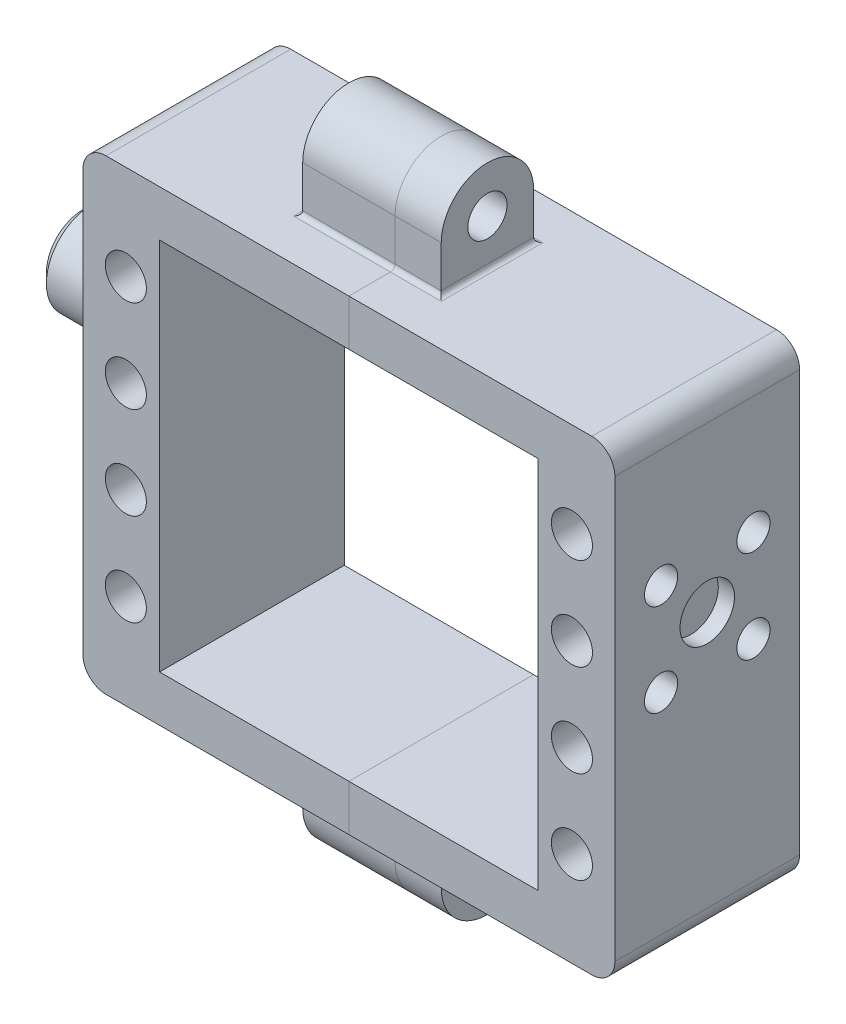
SolidWorks part; units mm, degrees
ref_plane "Front Plane" through (0, 0, 0) normal (0, 0, 1) x (1, 0, 0)
ref_plane "Top Plane" through (0, 0, 0) normal (0, 1, 0) x (1, 0, 0)
ref_plane "Right Plane" through (0, 0, 0) normal (1, 0, 0) x (0, 0, -1)
sketch "Sketch1" plane through (0, 0, 0) normal (0, 0, 1) x (1, 0, 0)
  line L0 (-8.3, -5) -> (49.3, -5)
  line L1 (0, 0) -> (41, 0)
  line L2 (0, 0) -> (0, 40.5)
  line L3 (0, 40.5) -> (41, 40.5)
  line L4 (41, 0) -> (41, 40.5)
  line L5 (49.3, -5) -> (49.3, 45.5)
  line L6 (-8.3, 45.5) -> (49.3, 45.5)
  line L7 (-8.3, -5) -> (-8.3, 45.5)
  line L8 (20.5, 45.5) -> (20.5, -5) construction
  line L10 (-3.65, 20.25) -> (-3.65, 25.25) construction
  line L11 (-3.65, 25.25) -> (-3.65, 35.25) construction
  circle A0 centre (-3.65, 25.25) radius 2.225
  circle A1 centre (-3.65, 35.25) radius 2.225
  circle A2 centre (-3.65, 5.25) radius 2.225
  circle A3 centre (-3.65, 15.25) radius 2.225
  circle A4 centre (44.65, 15.25) radius 2.225
  circle A5 centre (44.65, 5.25) radius 2.225
  circle A6 centre (44.65, 35.25) radius 2.225
  circle A7 centre (44.65, 25.25) radius 2.225
  point P34 (20.5, 20.25)
  dimension "D5" = 4.45
  dimension "D1" = 41
  dimension "D2" = 40.5
  dimension "D4" = 5
  dimension "D6" = 10
  dimension "D3" = 8.3
  dimension "D7" = 8.3
  dimension "D8" = 5
  dimension "D9" = 48.3
  dimension "D10" = 5
  dimension "D11" = 10
  dimension "D12" = 5
extrude "Boss-Extrude1" add sketch "Sketch1" along normal blind 20
fillet "Fillet1" radius 2.5 4 edges at (49.3, 45.5, 10) (49.3, -5, 10) (-8.3, -5, 10) (-8.3, 45.5, 10)
sketch "Sketch2" plane through (49.3, 0, 0) normal (-1, 0, 0) x (0, 0, 1)
  line L0 (20, 33.55) -> (0, 33.55) construction
  line L1 (20, 43) -> (20, -2.5) construction
  line L2 (0, 43) -> (0, -2.5) construction
  circle A0 centre (10, 33.55) radius 3.125
  circle A1 centre (10, 33.55) radius 5.125
  dimension "D1" = 6.25
  dimension "D2" = 38.55
  dimension "D3" = 2
ref_plane "Plane2" through (20.5, 0, 0) normal (-1, 0, 0) x (0, 0, 1)
sketch "Sketch8" plane through (20.5, 0, 0) normal (-1, 0, 0) x (0, 0, 1)
  line L0 (5, 45.5) -> (5, 50.5)
  line L1 (15, -5) -> (15, -10)
  line L2 (0, 45.5) -> (20, 45.5) construction
  line L3 (15, 45.5) -> (5, 45.5)
  line L4 (15, 45.5) -> (15, 50.5)
  line L5 (0, 20.25) -> (20, 20.25) construction
  line L6 (0, 43) -> (0, -2.5) construction
  line L7 (20, 43) -> (20, -2.5) construction
  line L8 (15, -5) -> (5, -5)
  line L9 (5, -5) -> (5, -10)
  arc A0 (15, 50.5) -> (5, 50.5) centre (10, 50.5) ccw
  circle A1 centre (10, 50.5) radius 2.125
  circle A2 centre (10, -10) radius 2.125
  arc A3 (15, -10) -> (5, -10) centre (10, -10) cw
  point P9 (10, 45.5)
  point P25 (10, -5)
  dimension "D1" = 4.25
  dimension "D2" = 10
  dimension "D3" = 5
extrude "Boss-Extrude3" add sketch "Sketch8" against normal blind 5 and the other way blind 10
fillet "Fillet5" radius 0.5 4 edges at (25.5, 45.5, 10) (18, 45.5, 5) (10.5, 45.5, 10) (18, 45.5, 15)
split "Split1" trim tools "Plane2" bodies to split 106 resulting bodies 107 108
sketch "Sketch9" plane through (10.5, 0, 0) normal (-1, 0, 0) x (0, 0, 1)
  line L0 (0, 20.25) -> (20, 20.25) construction
  line L1 (0, 43) -> (0, -2.5) construction
  line L2 (20, 43) -> (20, -2.5) construction
  circle A0 centre (10, 50.5) radius 2.95
  circle A1 centre (10, 50.5) radius 2.125 construction
  circle A2 centre (10, -10) radius 2.95
  dimension "D1" = 5.9
extrude "Cut-Extrude3" cut sketch "Sketch9" against normal up to next (10 mm away)
sketch "Sketch13" plane through (49.3, 0, 0) normal (1, 0, 0) x (0, 0, -1)
  line L0 (-15, 30.25) -> (-5, 20.25) construction
  line L1 (-5, 30.25) -> (-15, 20.25) construction
  line L2 (-20, 25.25) -> (0, 25.25) construction
  line L3 (-20, -2.5) -> (0, -2.5) construction
  circle A0 centre (-15, 30.25) radius 1.8
  circle A1 centre (-5, 30.25) radius 1.8
  circle A2 centre (-15, 20.25) radius 1.8
  circle A3 centre (-5, 20.25) radius 1.8
  point P11 (-10, 25.25)
  point P14 (-10, -2.5)
  dimension "D1" = 3.6
  dimension "D2" = 10
  dimension "D3" = 10
extrude "Cut-Extrude6" cut sketch "Sketch13" against normal up to next (8.3 mm away)
sketch "Sketch14" plane through (41, 0, 0) normal (-1, 0, 0) x (0, 0, 1)
  circle A0 centre (5, 30.25) radius 2.95
  circle A1 centre (15, 30.25) radius 2.95
  circle A2 centre (5, 20.25) radius 2.95
  circle A3 centre (15, 20.25) radius 2.95
  dimension "D1" = 5.9
extrude "Cut-Extrude7" cut sketch "Sketch14" against normal blind 5.5
sketch "Sketch15" plane through (49.3, 0, 0) normal (1, 0, 0) x (0, 0, -1)
  line L0 (-15, 30.25) -> (-5, 20.25) construction
  circle A0 centre (-10, 25.25) radius 2.95
  dimension "D1" = 5.9
extrude "Cut-Extrude8" cut sketch "Sketch15" against normal blind 1.75
sketch "Sketch16" plane through (-8.3, 0, 0) normal (-1, 0, 0) x (0, 0, 1)
  circle A0 centre (10, 25.25) radius 4.95
  circle A2 centre (10, 25.25) radius 2.95
  circle A3 centre (10, 25.25) radius 2.95
  dimension "D2" = 9.9
  dimension "D1" = 0
extrude "Boss-Extrude4" add sketch "Sketch16" along normal blind 10 contours A3 | A0 A3
fillet "Fillet6" radius 1 1 edges at (-8.3, 30.2, 10)
chamfer "Chamfer1" distance 1 angle 45 1 edges at (-18.3, 20.3, 10)
equation "\"D7@Sketch1\"=\"D3@Sketch1\""
